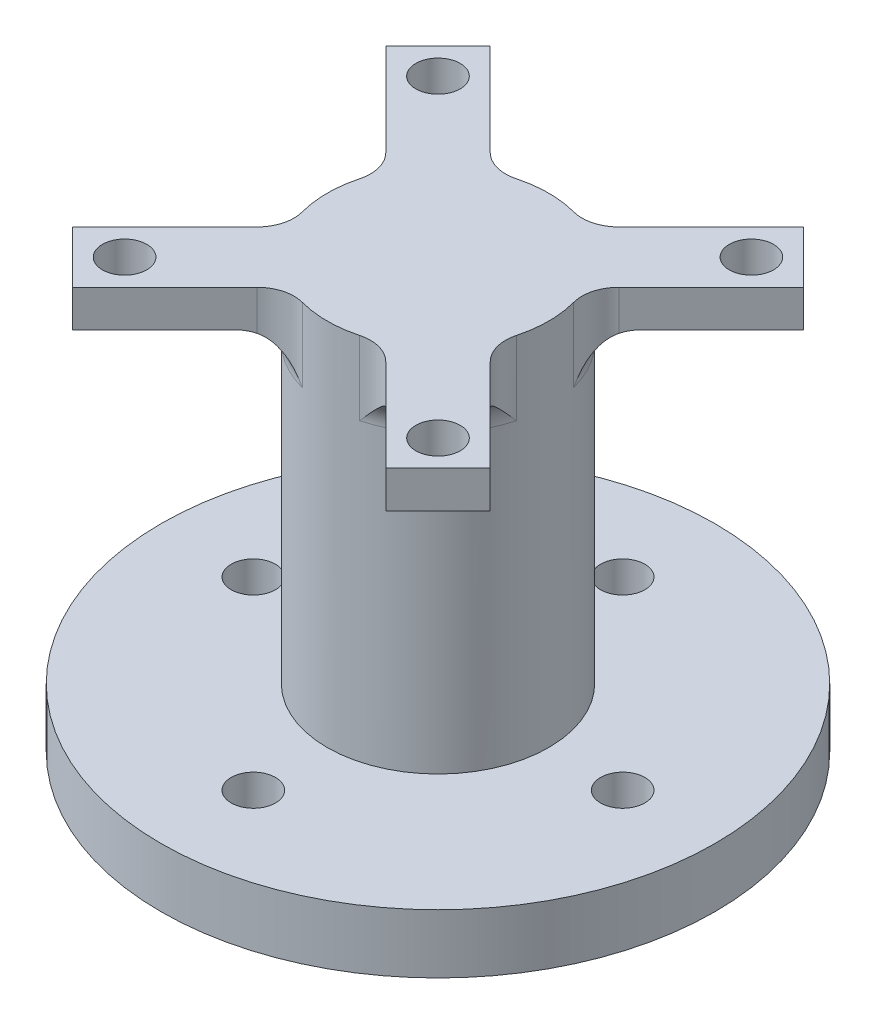
SolidWorks part; units mm, degrees
ref_plane "Front Plane" through (0, 0, 0) normal (0, 0, 1) x (1, 0, 0)
ref_plane "Top Plane" through (0, 0, 0) normal (0, 1, 0) x (1, 0, 0)
ref_plane "Right Plane" through (0, 0, 0) normal (1, 0, 0) x (0, 0, -1)
sketch "Sketch1" plane through (0, 0, 0) normal (0, 1, 0) x (1, 0, 0)
  circle A0 centre (0, 0) radius 37.5
  dimension "D1" = 75
extrude "Boss-Extrude1" add sketch "Sketch1" along normal blind 8
sketch "Sketch2" plane through (0, 8, 0) normal (0, 1, 0) x (1, 0, 0)
  circle A0 centre (0, 0) radius 25 construction
  circle A1 centre (25, 0) radius 3
  circle A2 centre (0, 25) radius 3
  circle A3 centre (-25, 0) radius 3
  circle A6 centre (0, -25) radius 3
  dimension "D1" = 50
  dimension "D2" = 6
  dimension "D3" = 6
  dimension "D4" = 6
  dimension "D10" = 6
  dimension "D7" = 90
  dimension "D5" = 90
  dimension "D6" = 90
extrude "Cut-Extrude1" cut sketch "Sketch2" against normal through all
sketch "Sketch3" plane through (0, 8, 0) normal (0, 1, 0) x (1, 0, 0)
  circle A0 centre (0, 0) radius 15
  dimension "D1" = 30
extrude "Boss-Extrude2" add sketch "Sketch3" along normal blind 50
sketch "Sketch7" plane through (0, 58, 0) normal (0, 1, 0) x (1, 0, 0)
  line L0 (-28.2843, 21.2132) -> (21.2132, -28.2843)
  line L1 (-28.2843, 21.2132) -> (-21.2132, 28.2843)
  line L2 (21.2132, -28.2843) -> (28.2843, -21.2132)
  line L3 (-21.2132, 28.2843) -> (28.2843, -21.2132)
  line L4 (-28.2843, 21.2132) -> (28.2843, -21.2132) construction
  line L5 (21.2132, -28.2843) -> (-21.2132, 28.2843) construction
  line L6 (0, 0) -> (15, 0) construction
  line L16 (-21.2132, -28.2843) -> (28.2843, 21.2132)
  line L17 (-21.2132, -28.2843) -> (-28.2843, -21.2132)
  line L18 (-28.2843, -21.2132) -> (21.2132, 28.2843)
  line L19 (28.2843, 21.2132) -> (21.2132, 28.2843)
  line L20 (-21.2132, -28.2843) -> (21.2132, 28.2843) construction
  line L21 (-28.2843, -21.2132) -> (28.2843, 21.2132) construction
  circle A0 centre (0, 0) radius 15 construction
  circle A1 centre (0, 0) radius 15 construction
  point P1 (0, 0)
  point P16 (0, 0)
  point P17 (28.2843, 48.833)
  point P18 (9.27, 29.0219)
  point P19 (3.2731, 30.8424)
  circle M8 centre (0, 0) radius 15
  dimension "D2" = 10
  dimension "D3" = 70
  dimension "D1" = 10
  dimension "D4" = 70
extrude "Boss-Extrude4" add sketch "Sketch7" against normal blind 5 contours L18 L17 L16 M8 | L18 L16 L0 M8 | L3 L0 L2 M8 | L18 L0 L16 L3 | L16 L0 L3 M8 | L16 L19 L18 M8 | L18 L3 L16 M8 | L3 L1 L0 M8 | L0 L18 L3 M8
sketch "Sketch5" plane through (0, 58, 0) normal (0, 1, 0) x (1, 0, 0)
  line L0 (-21.2132, 21.2132) -> (21.2132, -21.2132) construction
  line L1 (-30, 0) -> (30, 0) construction
  circle A0 centre (0, 0) radius 30 construction
  circle A1 centre (21.2132, -21.2132) radius 3
  circle A5 centre (-21.2132, 21.2132) radius 3
  circle A6 centre (-21.2132, -21.2132) radius 3
  circle A7 centre (21.2132, 21.2132) radius 3
  point P13 (0, 0)
  dimension "D2" = 6
  dimension "D4" = 6
  dimension "D1" = 60
  dimension "D6" = 6
  dimension "D5" = 6
  dimension "D3" = 45
extrude "Cut-Extrude2" cut sketch "Sketch5" against normal up to next
fillet "Fillet1" radius 5 12 edges at (-13.5355, 55.5, 6.4645) (6.4645, 55.5, -13.5355) (6.4645, 55.5, 13.5355) (-13.5355, 55.5, -6.4645) (13.5355, 55.5, 6.4645) (-6.4645, 55.5, -13.5355) (-6.4645, 55.5, 13.5355) (13.5355, 55.5, -6.4645) (-10.6066, 53, 10.6066) (10.6066, 53, -10.6066) (10.6066, 53, 10.6066) (-10.6066, 53, -10.6066)
equation "\"D4@Sketch2\"=\"D3@Sketch2\""
equation "\"D10@Sketch2\"=\"D3@Sketch2\""
equation "\"D1@Sketch7\"=\"D2@Sketch7\""
equation "\"D4@Sketch7\"=\"D3@Sketch7\""
equation "\"D4@Sketch5\"=\"D6@Sketch5\""
equation "\"D5@Sketch5\"=\"D6@Sketch5\""
equation "\"D6@Sketch5\"=\"D3@Sketch5\""
equation "\"D2@Sketch5\"=\"D3@Sketch5\""
